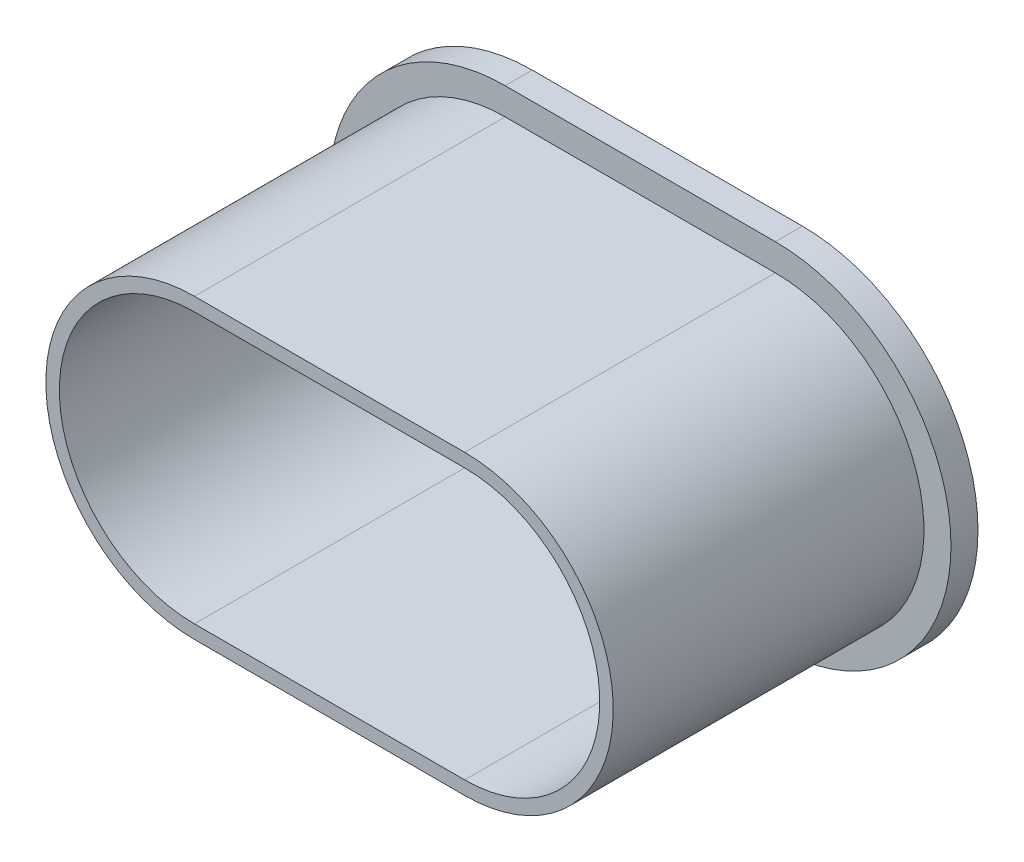
SolidWorks part; units mm, degrees
ref_plane "Front" through (0, 0, 0) normal (0, 0, 1) x (1, 0, 0)
ref_plane "Top" through (0, 0, 0) normal (0, 1, 0) x (1, 0, 0)
ref_plane "Right" through (0, 0, 0) normal (1, 0, 0) x (0, 0, -1)
sketch "草图1" plane through (0, 0, 0) normal (0, 0, 1) x (1, 0, 0)
  line L0 (-27.168, -13.4616) -> (-7.168, -13.4616)
  line L2 (-7.168, -16.4616) -> (-27.168, -16.4616)
  line L5 (-27.168, 6.5384) -> (-7.168, 6.5384)
  line L6 (-27.168, 9.5384) -> (-7.168, 9.5384)
  arc A0 (-27.168, -13.4616) -> (-27.168, 6.5384) centre (-27.168, -3.4616) cw
  arc A1 (-7.168, 6.5384) -> (-7.168, -13.4616) centre (-7.168, -3.4616) cw
  arc A2 (-27.168, -16.4616) -> (-27.168, 9.5384) centre (-27.168, -3.4616) cw
  arc A3 (-7.168, 9.5384) -> (-7.168, -16.4616) centre (-7.168, -3.4616) cw
extrude "凸台-拉伸1" add sketch "草图1" along normal blind 2
sketch "草图2" plane through (0, 0, 2) normal (0, 0, 1) x (1, 0, 0)
  line L0 (-27.168, 6.5384) -> (-7.168, 6.5384)
  line L2 (-7.168, -13.4616) -> (-27.168, -13.4616)
  line L5 (-27.168, 7.5384) -> (-7.168, 7.5384)
  line L7 (-27.168, -14.4616) -> (-7.168, -14.4616)
  arc A0 (-7.168, -13.4616) -> (-7.168, 6.5384) centre (-7.168, -3.4616) ccw construction
  arc A1 (-27.168, 6.5384) -> (-27.168, -13.4616) centre (-27.168, -3.4616) ccw
  arc A2 (-7.168, 6.5384) -> (-7.168, -13.4616) centre (-7.168, -3.4616) cw
  arc A3 (-27.168, -14.4616) -> (-27.168, 7.5384) centre (-27.168, -3.4616) cw
  arc A4 (-7.168, 7.5384) -> (-7.168, -14.4616) centre (-7.168, -3.4616) cw
extrude "凸台-拉伸2" add sketch "草图2" along normal blind 23
sketch "草图4" plane through (0, 0, 0) normal (0, 0, -1) x (-1, 0, 0)
  line L0 (17.168, -13.4616) -> (17.168, -14.4616)
  line L1 (27.168, -13.4616) -> (7.168, -13.4616) construction
  circle A0 centre (17.168, -14.4616) radius 0.3
extrude "切除-拉伸2" cut sketch "草图4" against normal blind 0.5
